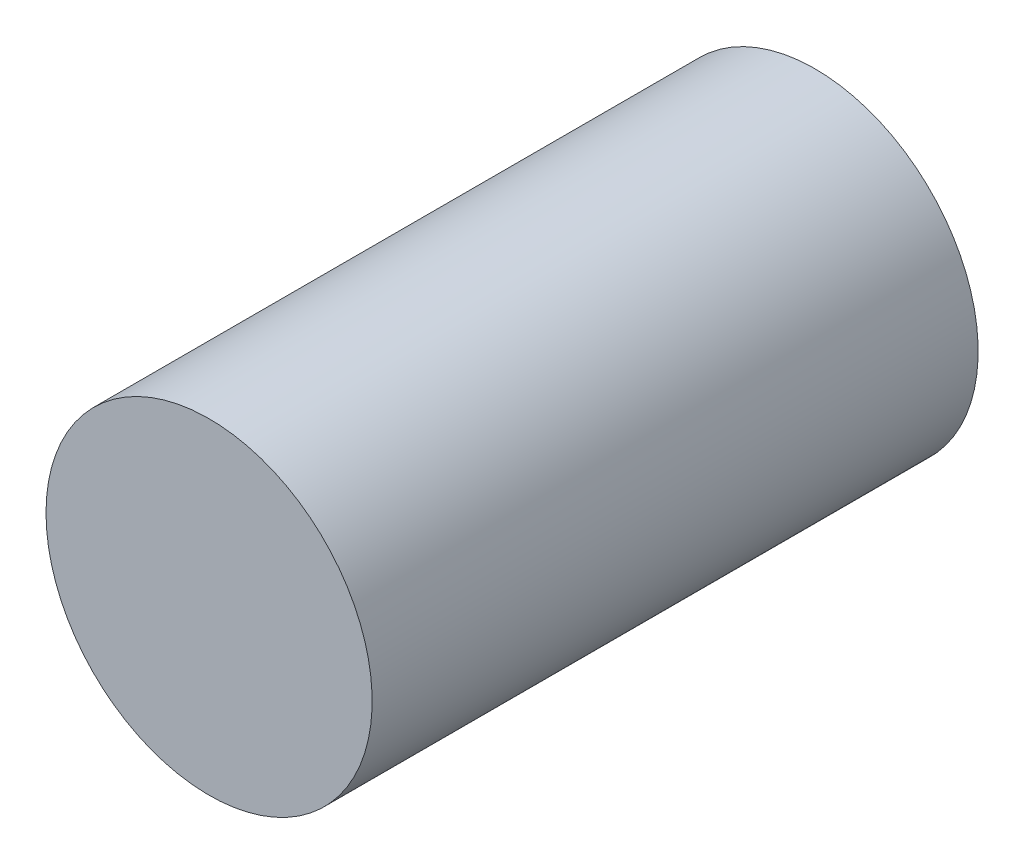
SolidWorks part; units mm, degrees
material "Alloy Steel"
ref_plane "Front Plane" through (0, 0, 0) normal (0, 0, 1) x (1, 0, 0)
ref_plane "Top Plane" through (0, 0, 0) normal (0, 1, 0) x (1, 0, 0)
ref_plane "Right Plane" through (0, 0, 0) normal (1, 0, 0) x (0, 0, -1)
sketch "Sketch1" plane through (0, 0, 0) normal (0, 0, 1) x (1, 0, 0)
  circle A0 centre (0, 0) radius 6.7277
  dimension "D1" = 13.4554
extrude "Boss-Extrude1" add sketch "Sketch1" along normal mid plane 25 contours A0
